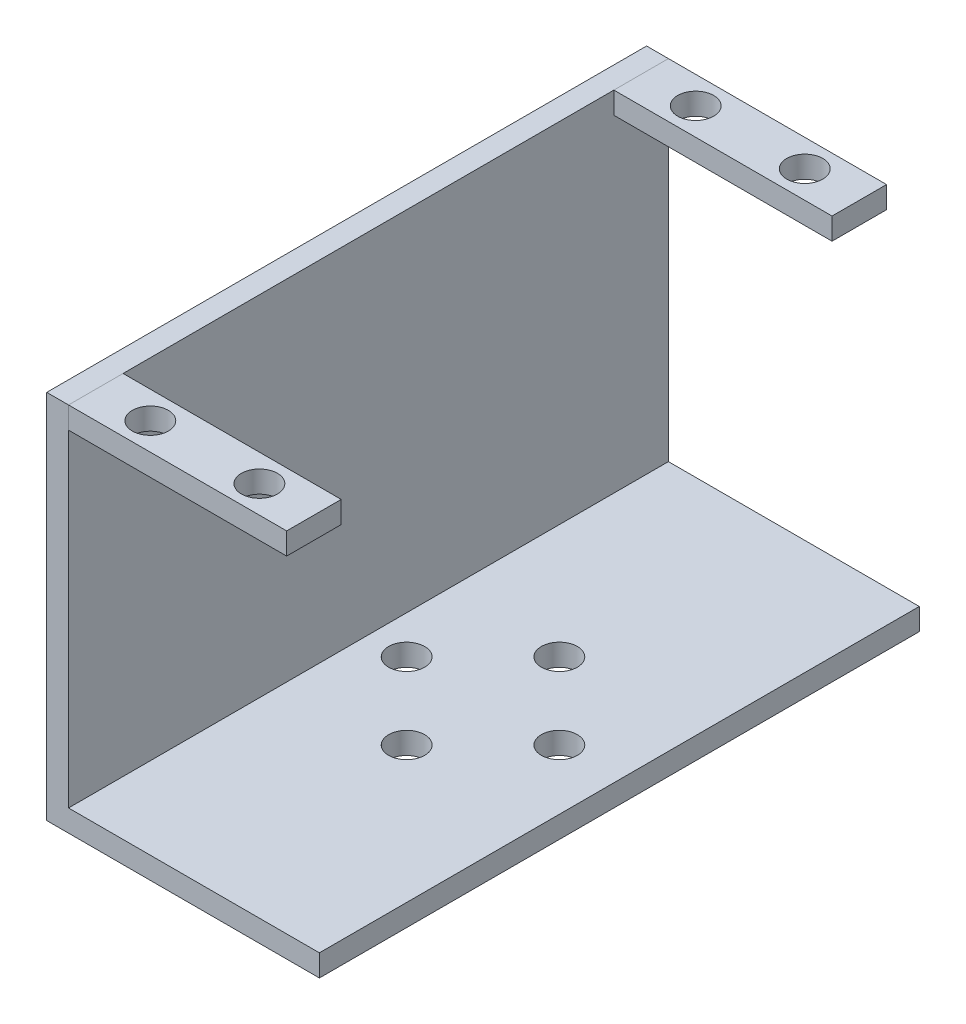
SolidWorks part; units mm, degrees
ref_plane "前视基准面" through (0, 0, 0) normal (0, 0, 1) x (1, 0, 0)
ref_plane "上视基准面" through (0, 0, 0) normal (0, 1, 0) x (1, 0, 0)
ref_plane "右视基准面" through (0, 0, 0) normal (1, 0, 0) x (0, 0, -1)
sketch "草图1" plane through (0, 0, 0) normal (0, 1, 0) x (1, 0, 0)
  line L1 (-12.5, -27.5) -> (12.5, -27.5)
  line L2 (-12.5, -27.5) -> (-12.5, 27.5)
  line L3 (-12.5, 27.5) -> (12.5, 27.5)
  line L4 (12.5, -27.5) -> (12.5, 27.5)
  line L5 (-12.5, -27.5) -> (12.5, 27.5) construction
  line L6 (-12.5, 27.5) -> (12.5, -27.5) construction
  point P1 (0, 0)
  dimension "D1" = 55
  dimension "D2" = 25
extrude "凸台-拉伸1" add sketch "草图1" along normal blind 2
sketch "草图2" plane through (0, 2, 0) normal (0, 1, 0) x (1, 0, 0)
  line L0 (12.5, 0) -> (-12.5, 0) construction
  line L1 (12.5, -27.5) -> (12.5, 27.5) construction
  line L2 (-12.5, 27.5) -> (-12.5, -27.5) construction
  line L3 (0, 27.5) -> (0, -27.5) construction
  line L4 (12.5, 27.5) -> (-12.5, 27.5) construction
  line L5 (-12.5, -27.5) -> (12.5, -27.5) construction
  circle A0 centre (7, 0) radius 1.65
  circle A1 centre (0, 7) radius 1.65
  circle A2 centre (-7, 0) radius 1.65
  circle A3 centre (0, -7) radius 1.65
  dimension "D1" = 3.3
  dimension "D2" = 3.3
  dimension "D4" = 3.3
  dimension "D5" = 3.3
  dimension "D3" = 7
  dimension "D6" = 7
  dimension "D7" = 7
  dimension "D8" = 7
extrude "切除-拉伸1" cut sketch "草图2" against normal blind 2
sketch "草图3" plane through (0, 2, 0) normal (0, 1, 0) x (1, 0, 0)
  line L0 (-12.5, -27.5) -> (12.5, -27.5) construction
  line L1 (-12.5, 27.5) -> (-10.5, 27.5)
  line L2 (-12.5, 27.5) -> (-12.5, -27.5)
  line L3 (-12.5, -27.5) -> (-10.5, -27.5)
  line L4 (-10.5, 27.5) -> (-10.5, -27.5)
  dimension "D1" = 2
extrude "凸台-拉伸2" add sketch "草图3" along normal blind 32
sketch "草图4" plane through (-10.5, 0, 0) normal (1, 0, 0) x (0, 0, -1)
  line L0 (0, 34) -> (0, 2) construction
  line L1 (-27.5, 34) -> (27.5, 34) construction
  line L2 (-27.5, 2) -> (27.5, 2) construction
  line L3 (-22.5, 32) -> (22.5, 32) construction
  line L4 (22.5, 34) -> (27.5, 34)
  line L5 (-22.5, 32) -> (-27.5, 32)
  line L6 (-22.5, 32) -> (-22.5, 34)
  line L7 (-22.5, 34) -> (-27.5, 34)
  line L8 (-27.5, 32) -> (-27.5, 34)
  line L9 (27.5, 32) -> (27.5, 34)
  line L10 (22.5, 32) -> (27.5, 32)
  line L11 (22.5, 32) -> (22.5, 34)
  line L12 (-27.5, 2) -> (27.5, 2) construction
  dimension "D1" = 45
  dimension "D2" = 5
  dimension "D3" = 2
  dimension "D4" = 30
extrude "凸台-拉伸3" add sketch "草图4" along normal blind 20 separate body
sketch "草图5" plane through (0, 34, 0) normal (0, 1, 0) x (1, 0, 0)
  line L0 (-10.5, -25) -> (9.5, -25) construction
  line L1 (-10.5, -22.5) -> (-10.5, -27.5) construction
  line L2 (9.5, -22.5) -> (9.5, -27.5) construction
  line L3 (-12.5, 0) -> (-10.5, 0) construction
  line L4 (-12.5, 27.5) -> (-12.5, -27.5) construction
  line L5 (-10.5, -27.5) -> (-10.5, 27.5) construction
  circle A0 centre (-5.5, -25) radius 1.65
  circle A1 centre (4.5, -25) radius 1.65
  circle A2 centre (4.5, 25) radius 1.65
  circle A3 centre (-5.5, 25) radius 1.65
  dimension "D1" = 3.3
  dimension "D2" = 3.3
  dimension "D3" = 10
  dimension "D4" = 5
extrude "切除-拉伸2" cut sketch "草图5" against normal up to next (2 mm away)
